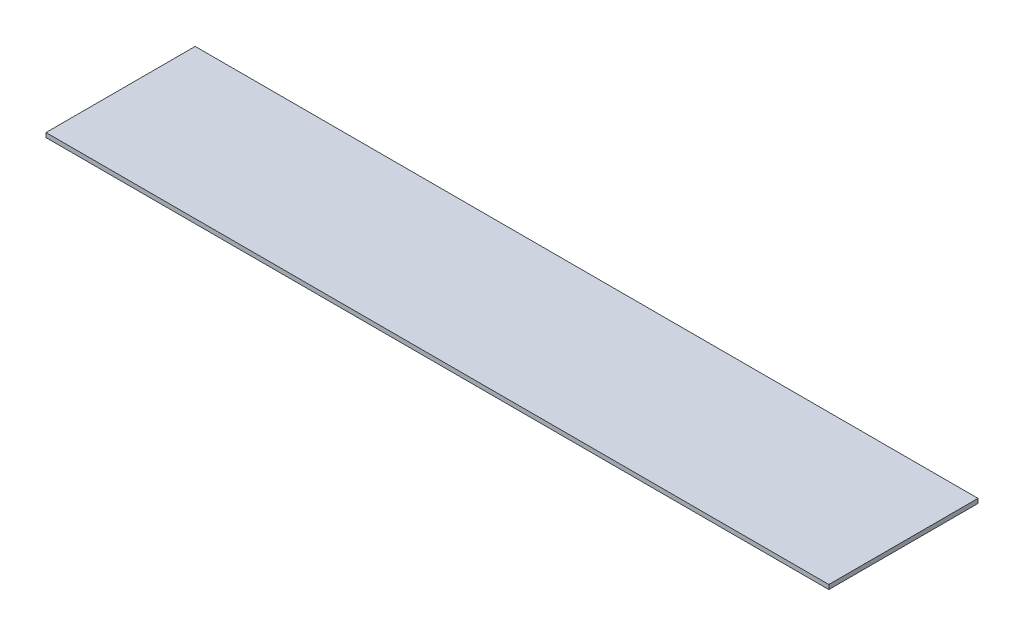
SolidWorks part; units mm, degrees
ref_plane "Alzado" through (0, 0, 0) normal (0, 0, 1) x (1, 0, 0)
ref_plane "Planta" through (0, 0, 0) normal (0, 1, 0) x (1, 0, 0)
ref_plane "Vista lateral" through (0, 0, 0) normal (1, 0, 0) x (0, 0, -1)
sketch "Croquis1" plane through (0, 0, 0) normal (0, 1, 0) x (1, 0, 0)
  line L1 (265, -50.5) -> (-265, -50.5)
  line L2 (265, -50.5) -> (265, 50.5)
  line L3 (265, 50.5) -> (-265, 50.5)
  line L4 (-265, -50.5) -> (-265, 50.5)
  line L5 (265, -50.5) -> (-265, 50.5) construction
  line L6 (265, 50.5) -> (-265, -50.5) construction
  point P0 (0, 0)
extrude "Saliente-Extruir1" add sketch "Croquis1" along normal blind 3
